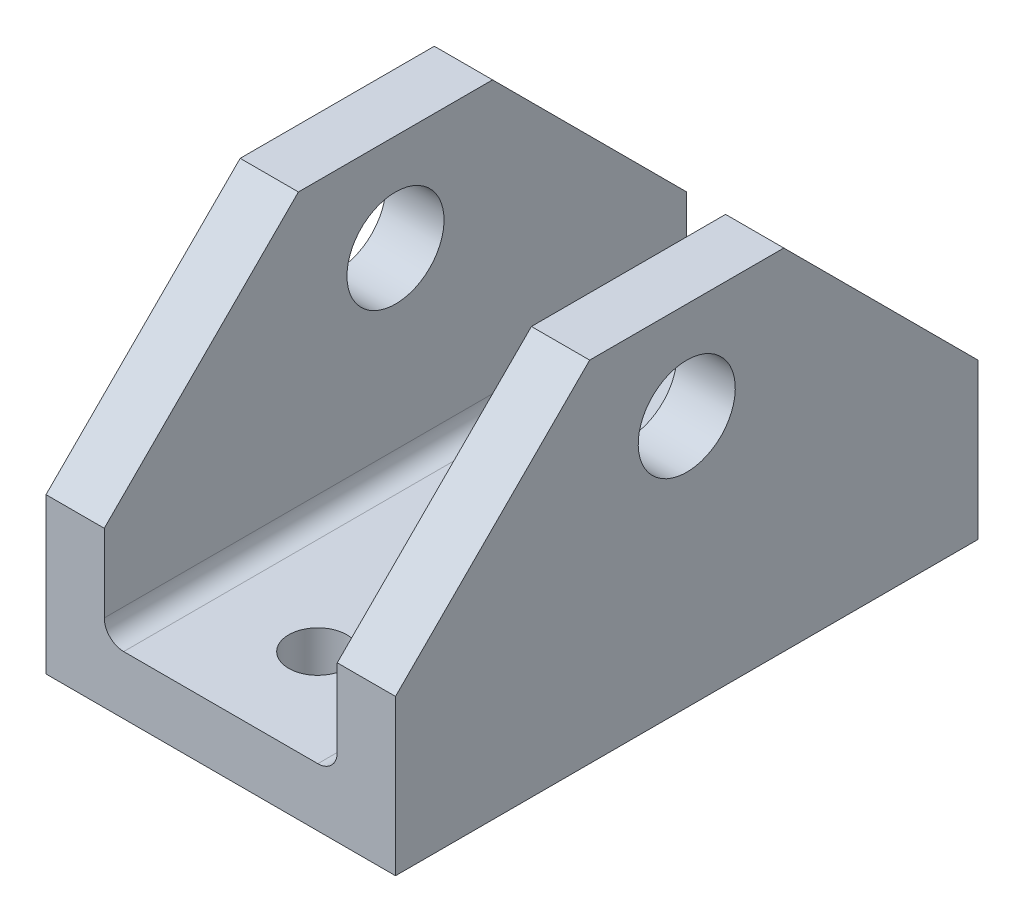
SolidWorks part; units mm, degrees
ref_plane "Front Plane" through (0, 0, 0) normal (0, 0, 1) x (1, 0, 0)
ref_plane "Top Plane" through (0, 0, 0) normal (0, 1, 0) x (1, 0, 0)
ref_plane "Right Plane" through (0, 0, 0) normal (1, 0, 0) x (0, 0, -1)
sketch "Sketch1" plane through (0, 0, 0) normal (0, 0, 1) x (1, 0, 0)
  line L0 (-6, 0) -> (6, 0)
  line L1 (6, 0) -> (6, 15)
  line L2 (6, 15) -> (9, 15)
  line L3 (9, 15) -> (9, -3)
  line L4 (9, -3) -> (-9, -3)
  line L5 (0, -55) -> (0, 55) construction
  line L6 (-6, 15) -> (-9, 15)
  line L7 (-6, 0) -> (-6, 15)
  line L8 (-9, 15) -> (-9, -3)
  point P0 (0, -3)
  point P13 (0, 0)
  dimension "D1" = 6
  dimension "D2" = 15
  dimension "D3" = 3
  dimension "D4" = 18
extrude "Boss-Extrude1" add sketch "Sketch1" along normal mid plane 30
sketch "Sketch3" plane through (0, 0, 0) normal (0, 1, 0) x (1, 0, 0)
  line L0 (0, 0) -> (0, 10) construction
  line L1 (-55, 0) -> (55, 0) construction
  circle A0 centre (0, 10) radius 1.5
  circle A1 centre (0, -10) radius 1.5
  dimension "D2" = 3
  dimension "D1" = 10
extrude "Cut-Extrude1" cut sketch "Sketch3" against normal blind 3
sketch "Sketch4" plane through (9, 0, 0) normal (1, 0, 0) x (0, 0, -1)
  line L0 (0, 0) -> (0, 10) construction
  line L2 (-15, 15) -> (-5, 15)
  line L3 (-15, 15) -> (15, 15) construction
  line L5 (-15, 15) -> (-15, 5)
  line L6 (-15, -3) -> (-15, 15) construction
  line L7 (-15, 5) -> (-5, 15)
  line L8 (15, 5) -> (5, 15)
  line L9 (15, 15) -> (15, 5)
  line L10 (15, 15) -> (5, 15)
  circle A0 centre (0, 10) radius 2.5
  dimension "D2" = 5
  dimension "D1" = 10
  dimension "D3" = 10
  dimension "D4" = 10
extrude "Cut-Extrude2" cut sketch "Sketch4" against normal up to surface (18 mm away) up to face at (-9, 6, 0)
fillet "Fillet1" radius 1 2 edges at (6, 0, 0) (-6, 0, 0)
